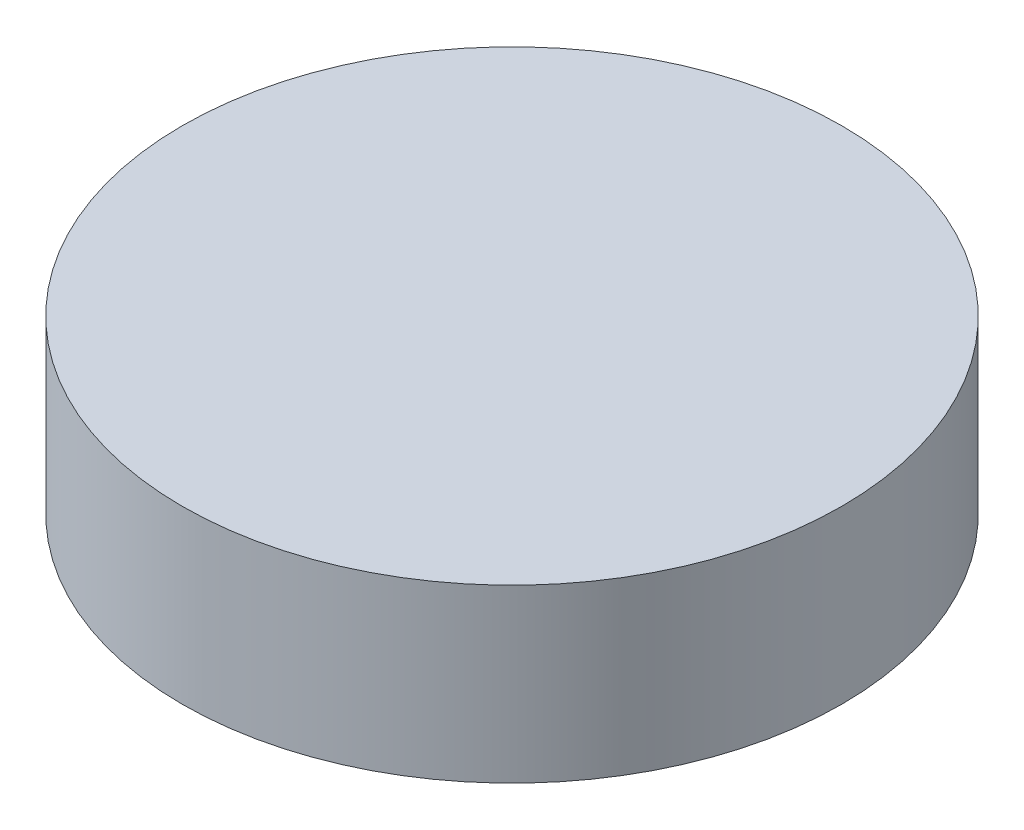
SolidWorks part; units mm, degrees
material "Gray Cast Iron"
ref_plane "Front" through (0, 0, 0) normal (0, 0, 1) x (1, 0, 0)
ref_plane "Top" through (0, 0, 0) normal (0, 1, 0) x (1, 0, 0)
ref_plane "Right" through (0, 0, 0) normal (1, 0, 0) x (0, 0, -1)
sketch "Sketch1" plane through (0, 0, 0) normal (0, 1, 0) x (1, 0, 0)
  circle A0 centre (0, 0) radius 7.5
  dimension "D1" = 15
extrude "Boss-Extrude1" add sketch "Sketch1" along normal blind 5
sketch "Sketch2" plane through (0, 5, 0) normal (0, 1, 0) x (1, 0, 0)
  circle A0 centre (0, 0) radius 25
  dimension "D1" = 50
extrude "Boss-Extrude2" add sketch "Sketch2" along normal blind 13
